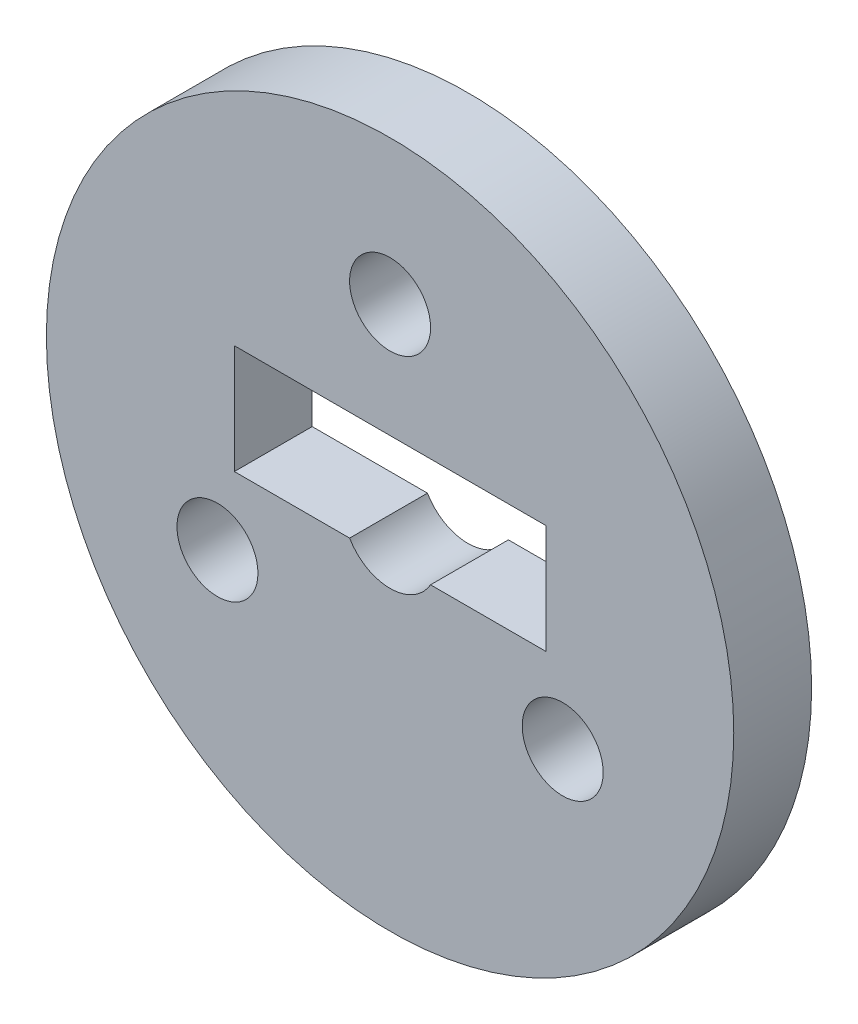
SolidWorks part; units mm, degrees
ref_plane "정면" through (0, 0, 0) normal (0, 0, 1) x (1, 0, 0)
ref_plane "윗면" through (0, 0, 0) normal (0, 1, 0) x (1, 0, 0)
ref_plane "우측면" through (0, 0, 0) normal (1, 0, 0) x (0, 0, -1)
sketch "스케치1" plane through (0, 0, 0) normal (0, 0, 1) x (1, 0, 0)
  line L0 (0, 0) -> (0, 33.5972) construction
  line L1 (0, 0) -> (-11.0851, -6.4) construction
  line L7 (10, 5.5) -> (-10, 5.5)
  line L8 (10, 5.5) -> (10, -1.5)
  line L9 (10, -1.5) -> (-10, -1.5)
  line L10 (-10, 5.5) -> (-10, -1.5)
  line L11 (10, 5.5) -> (-10, -1.5) construction
  line L12 (10, -1.5) -> (-10, 5.5) construction
  circle A0 centre (0, 0) radius 22.0716
  circle A1 centre (0, 12.8) radius 2.6
  circle A2 centre (0, 0) radius 15.95
  circle A3 centre (11.0851, -6.4) radius 2.6
  circle A4 centre (-11.0851, -6.4) radius 2.6
  circle A5 centre (0, 0) radius 3
  point P0 (0, 2)
  point P14 (0, 0)
  dimension "D1" = 5.2
  dimension "D2" = 31.9
  dimension "D3" = 44.1433
  dimension "D4" = 12.8
  dimension "D6" = 20
  dimension "D7" = 7
  dimension "D9" = 6
  dimension "D8" = 2
  dimension "D5" = 3
extrude "보스-돌출1" add sketch "스케치1" along normal blind 5
